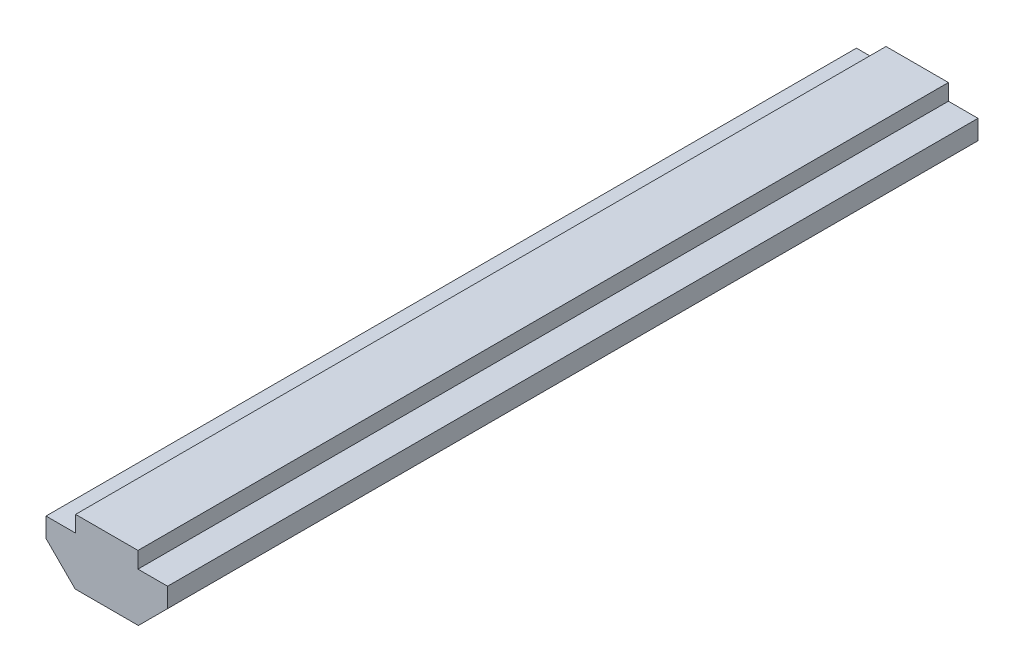
SolidWorks part; units mm, degrees
ref_plane "前视基准面" through (0, 0, 0) normal (0, 0, 1) x (1, 0, 0)
ref_plane "上视基准面" through (0, 0, 0) normal (0, 1, 0) x (1, 0, 0)
ref_plane "右视基准面" through (0, 0, 0) normal (1, 0, 0) x (0, 0, -1)
sketch "草图1" plane through (0, 0, 0) normal (0, 0, 1) x (1, 0, 0)
  line B0 (11.4, -6) -> (15, -2.4)
  line B1 (15, -2.4) -> (15, 0)
  line B2 (15, 0) -> (11.35, 0)
  line B3 (11.35, 0) -> (11.35, 2)
  line B4 (11.35, 2) -> (3.65, 2)
  line B5 (3.65, 2) -> (3.65, 0)
  line B6 (3.65, 0) -> (0, 0)
  line B7 (0, 0) -> (0, -2.4)
  line B8 (0, -2.4) -> (3.6, -6)
  line B9 (3.6, -6) -> (11.4, -6)
sketch_block_instance "A$C379F4245-1"
sketch_block "A$C379F4245"
extrude "凸台-拉伸1" add sketch "草图1" along normal blind 100
